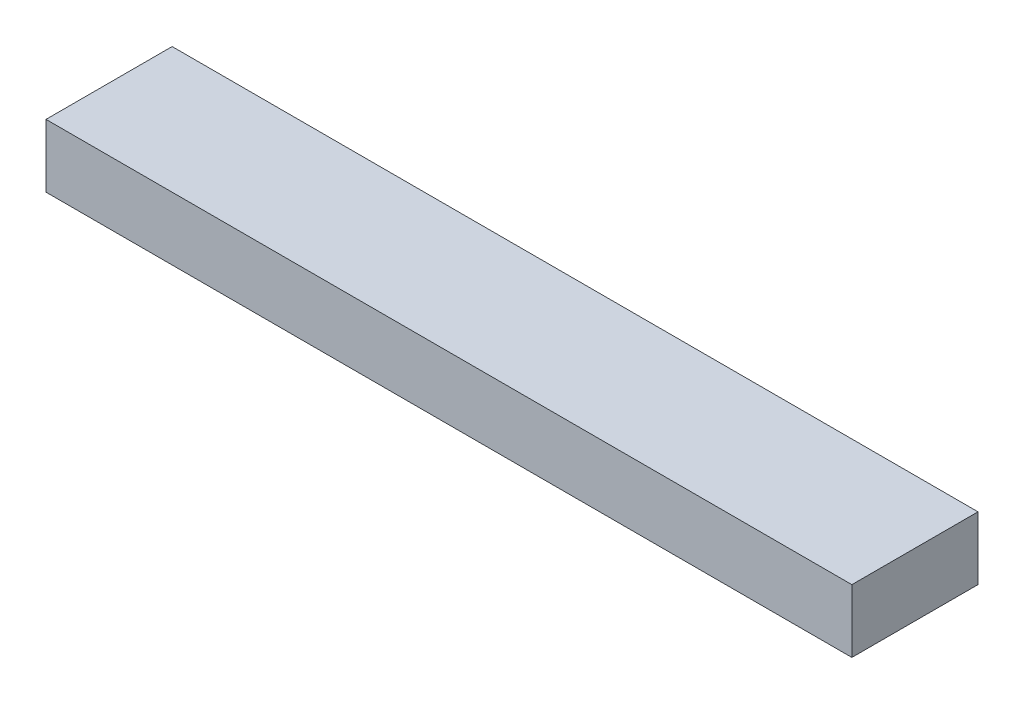
SolidWorks part; units mm, degrees
ref_plane "Front Plane" through (0, 0, 0) normal (0, 0, 1) x (1, 0, 0)
ref_plane "Top Plane" through (0, 0, 0) normal (0, 1, 0) x (1, 0, 0)
ref_plane "Right Plane" through (0, 0, 0) normal (1, 0, 0) x (0, 0, -1)
other "Configuration Table"
sketch "Sketch1" plane through (0, 0, 0) normal (0, 0, 1) x (1, 0, 0)
  line L1 (120, 470) -> (580, 470)
  line L2 (120, 470) -> (120, 506)
  line L3 (120, 506) -> (580, 506)
  line L4 (580, 470) -> (580, 506)
extrude "PACK_boyunduruk_profil_36x72_1" add sketch "Sketch1" against normal blind 72 from offset 364 separate body
